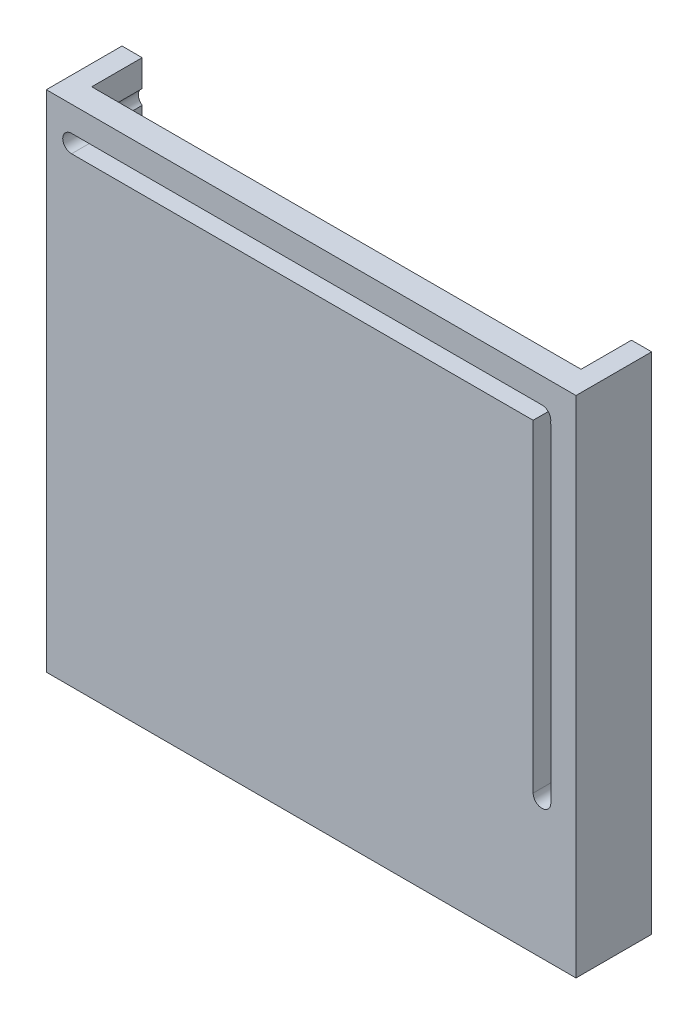
SolidWorks part; units mm, degrees
material "Balsa"
ref_plane "Plan de face" through (0, 0, 0) normal (0, 0, 1) x (1, 0, 0)
ref_plane "Plan de dessus" through (0, 0, 0) normal (0, 1, 0) x (1, 0, 0)
ref_plane "Plan de droite" through (0, 0, 0) normal (1, 0, 0) x (0, 0, -1)
sketch "Sketch1" plane through (0, 0, 0) normal (0, 0, 1) x (1, 0, 0)
  line L1 (-105, -100) -> (105, -100)
  line L2 (-105, -100) -> (-105, 100)
  line L3 (-105, 100) -> (105, 100)
  line L4 (105, -100) -> (105, 100)
  line L5 (-105, -100) -> (105, 100) construction
  line L6 (-105, 100) -> (105, -100) construction
  point P0 (0, 0)
  dimension "D1" = 210
  dimension "D2" = 200
extrude "Boss-Extrude1" add sketch "Sketch1" along normal blind 30
sketch "Sketch2" plane through (0, -100, 0) normal (0, -1, 0) x (-1, 0, 0)
  line L0 (105, 0) -> (-105, 0) construction
  line L1 (97, 0) -> (-97, 0)
  line L2 (97, 0) -> (97, -20)
  line L3 (97, -20) -> (-97, -20)
  line L4 (-97, 0) -> (-97, -20)
  line L5 (97, 0) -> (-97, -20) construction
  line L6 (97, -20) -> (-97, 0) construction
  line L7 (105, -30) -> (105, 0) construction
  line L8 (-105, -30) -> (-105, 0) construction
  point P0 (0, -10)
  dimension "D1" = 20
  dimension "D2" = 8
  dimension "D3" = 8
extrude "Cut-Extrude1" cut sketch "Sketch2" against normal through all
sketch "Sketch3" plane through (0, 0, 30) normal (0, 0, 1) x (1, 0, 0)
  line L0 (88, 85) -> (88, -45)
  line L1 (95, 85) -> (95, -45)
  line L2 (105, -100) -> (105, 100) construction
  line L3 (105, 100) -> (-105, 100) construction
  line L4 (-105, -100) -> (105, -100) construction
  arc A0 (95, 85) -> (88, 85) centre (91.5, 85) ccw
  arc A1 (95, -45) -> (88, -45) centre (91.5, -45) cw
  dimension "D3" = 15
  dimension "D1" = 10
  dimension "D2" = 7
  dimension "D4" = 55
extrude "Cut-Extrude2" cut sketch "Sketch3" against normal through all
sketch "Sketch4" plane through (0, 0, 30) normal (0, 0, 1) x (1, 0, 0)
  line L0 (91.5, 83) -> (-95, 83)
  line L1 (91.5, 90) -> (-95, 90)
  line L2 (105, 100) -> (-105, 100) construction
  line L3 (-105, 100) -> (-105, -100) construction
  line L4 (105, -100) -> (105, 100) construction
  arc A0 (91.5, 83) -> (91.5, 90) centre (91.5, 86.5) ccw
  arc A1 (-95, 83) -> (-95, 90) centre (-95, 86.5) cw
  dimension "D1" = 10
  dimension "D2" = 7
  dimension "D3" = 10
  dimension "D4" = 13.5
extrude "Cut-Extrude3" cut sketch "Sketch4" against normal through all
sketch "Sketch5" plane through (0, -100, 0) normal (0, -1, 0) x (1, 0, 0)
  line L0 (-105, 30) -> (-105, 0) construction
  circle A0 centre (-6, 24.5446) radius 2.5
  circle A1 centre (14, 24.5446) radius 2.5
  point P6 (0, 0)
  dimension "D3" = 5
  dimension "D4" = 5
  dimension "D1" = 20
  dimension "D2" = 99
extrude "Cut-Extrude4" cut sketch "Sketch5" against normal blind 10
